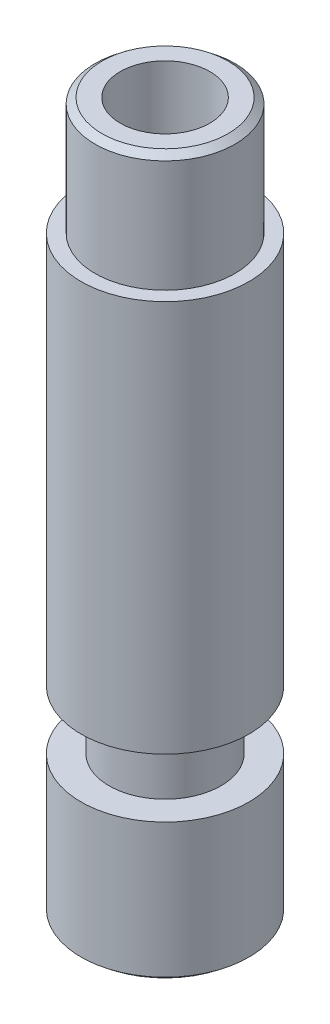
SolidWorks part; units mm, degrees
material "AISI 347 Annealed Stainless Steel (SS)"
ref_plane "Front Plane" through (0, 0, 0) normal (0, 0, 1) x (1, 0, 0)
ref_plane "Top Plane" through (0, 0, 0) normal (0, 1, 0) x (1, 0, 0)
ref_plane "Right Plane" through (0, 0, 0) normal (1, 0, 0) x (0, 0, -1)
sketch "Sketch1" plane through (0, 0, 0) normal (0, 0, 1) x (1, 0, 0)
  line L0 (3, 0.2) -> (2.75, 0)
  line L1 (3, 0.2) -> (3, 5)
  line L2 (3, 5) -> (2, 5)
  line L3 (2, 5) -> (2, 7.1)
  line L4 (2, 7.1) -> (3, 7.1)
  line L5 (3, 7.1) -> (3, 21.1)
  line L6 (3, 21.1) -> (2.5, 21.1)
  line L7 (2.5, 21.1) -> (2.5, 25.1)
  line L8 (2.5, 25.1) -> (2.25, 25.3)
  line L9 (2.25, 25.3) -> (0, 25.3)
  line L10 (0, 25.3) -> (0, 0)
  line L11 (0, 0) -> (0, 1091.2099) construction
  line L12 (2.75, 0) -> (0, 0)
  dimension "D1" = 6
  dimension "D2" = 5
  dimension "D3" = 18
  dimension "D4" = 2.1
  dimension "D5" = 0.2
  dimension "D6" = 14
  dimension "D7" = 0.2
  dimension "D8" = 4.5
  dimension "D9" = 4
  dimension "D10" = 7.1
revolve "Revolve1" add sketch "Sketch1" angle 360 about L11
sketch "Sketch3" plane through (0, 25.3, 0) normal (0, 1, 0) x (1, 0, 0)
  circle A0 centre (0, 0) radius 1.6
  dimension "D1" = 3.2
extrude "Cut-Extrude1" cut sketch "Sketch3" against normal through all
equation "\"D5@Sketch1\"=\"D7@Sketch1\""
